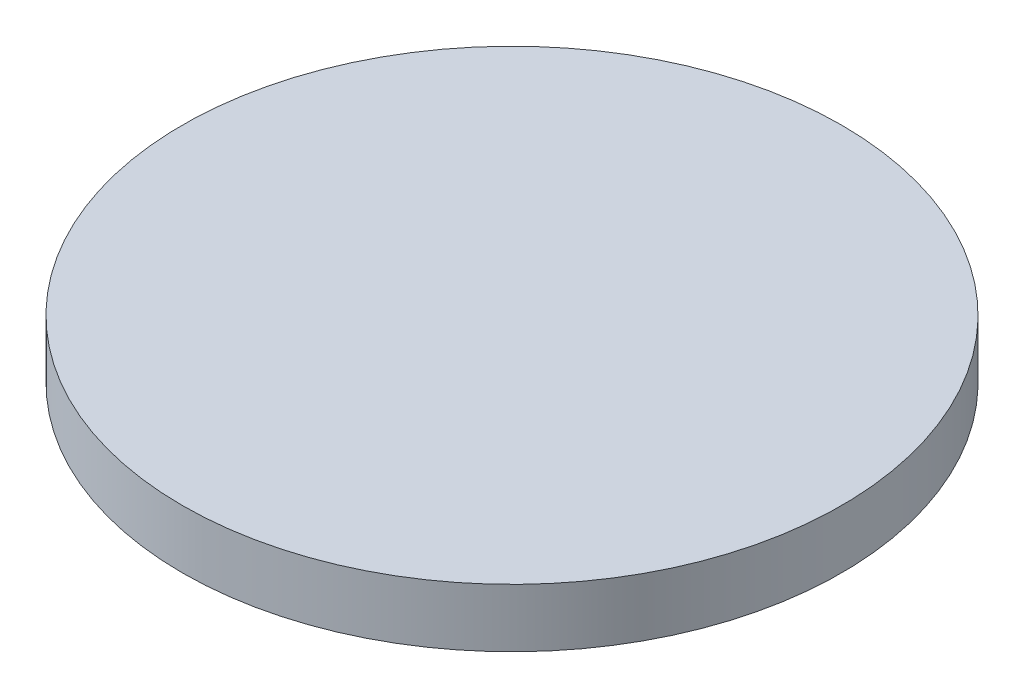
SolidWorks part; units mm, degrees
material "Alloy Steel"
ref_plane "Front Plane" through (0, 0, 0) normal (0, 0, 1) x (1, 0, 0)
ref_plane "Top Plane" through (0, 0, 0) normal (0, 1, 0) x (1, 0, 0)
ref_plane "Right Plane" through (0, 0, 0) normal (1, 0, 0) x (0, 0, -1)
sketch "Sketch1" plane through (0, 0, 0) normal (0, 1, 0) x (1, 0, 0)
  circle A0 centre (0, 0) radius 11.292
  dimension "D1" = 22.584
extrude "Boss-Extrude1" add sketch "Sketch1" along normal blind 2
